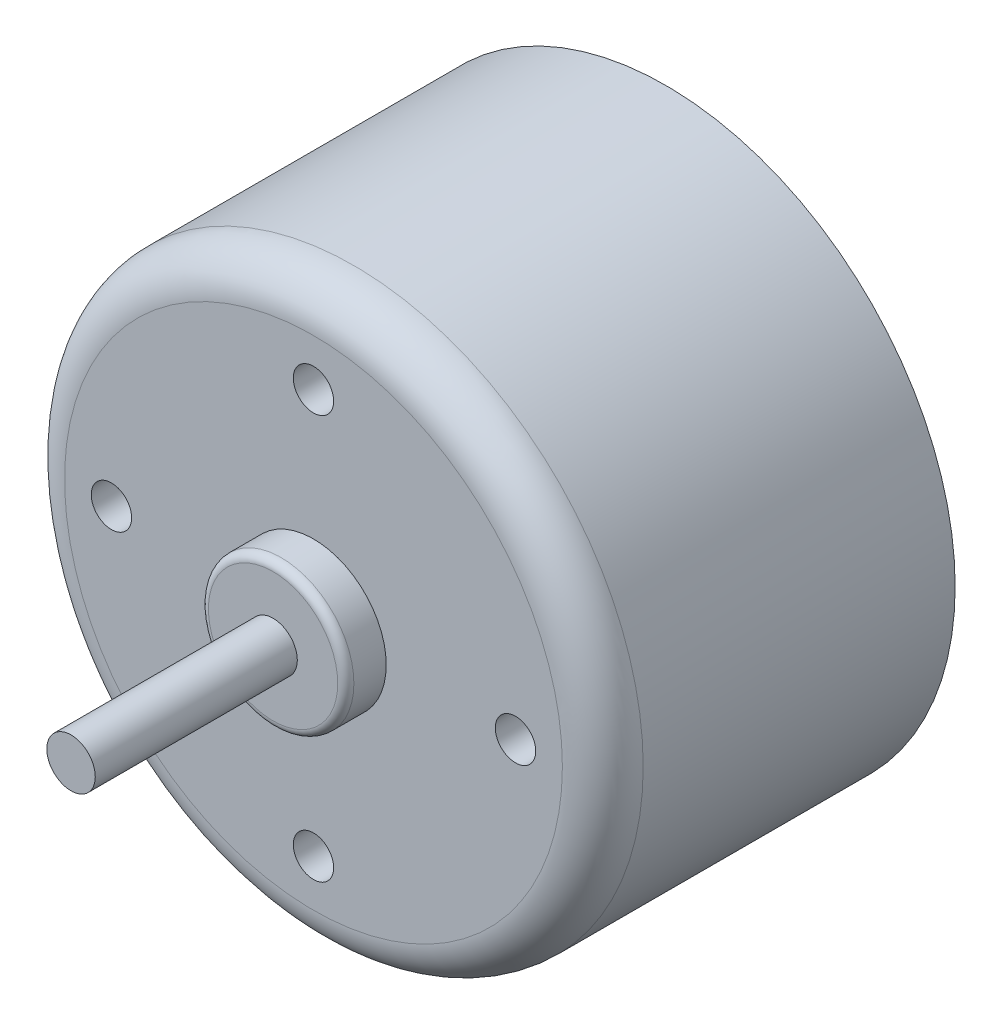
SolidWorks part; units mm, degrees
ref_plane "Front Plane" through (0, 0, 0) normal (0, 0, 1) x (1, 0, 0)
ref_plane "Top Plane" through (0, 0, 0) normal (0, 1, 0) x (1, 0, 0)
ref_plane "Right Plane" through (0, 0, 0) normal (1, 0, 0) x (0, 0, -1)
sketch "Sketch1" plane through (0, 0, 0) normal (0, 0, 1) x (1, 0, 0)
  circle A0 centre (0, 0) radius 17.9
  dimension "D1" = 35.8
extrude "Boss-Extrude1" add sketch "Sketch1" along normal blind 21.8
fillet "Fillet1" radius 2.5 1 edges at (17.9, 0, 21.8)
sketch "Sketch2" plane through (0, 0, 21.8) normal (0, 0, 1) x (1, 0, 0)
  circle A0 centre (0, 0) radius 4.5
  dimension "D1" = 9
extrude "Boss-Extrude2" add sketch "Sketch2" along normal blind 2.5
fillet "Fillet2" radius 0.5 1 edges at (4.5, 0, 24.3)
hole_wizard "M3x0.5 Tapped Hole1" positions "Sketch3" profile "Sketch4" tap size "M3x0.5" standard "ANSI Metric"
sketch "Sketch3" plane through (0, 0, 21.8) normal (0, 0, 1) x (1, 0, 0)
  circle A0 centre (0, 0) radius 12.5
  point P0 (0, 12.5)
  point P8 (0, -12.5)
  point P10 (12.5, 0)
  point P12 (-12.5, 0)
  dimension "D1" = 25
sketch "Sketch4" plane through (0, 12.5, 21.8) normal (1, 0, 0) x (0, -1, 0)
  line L0 (0, 0) -> (0, 8.3711)
  line L1 (0, 8.3711) -> (1.25, 7.62)
  line L2 (1.25, 7.62) -> (1.25, 0)
  line L5 (1.25, 0) -> (0, 0)
  line L10 (0, 8.3711) -> (-1.25, 7.62) construction
  line L11 (0, -6.35) -> (0, 107.95) construction
  dimension "Tap Drill Dia." = 2.5
  dimension "Tap Drill Depth" = 7.62
  dimension "Drill Angle" = 118
cosmetic thread "Hole Thread1" parameters "D1"=6.096, "D2"=3
cosmetic thread "Hole Thread2" parameters "D1"=6.096, "D2"=3
cosmetic thread "Hole Thread3" parameters "D1"=6.096, "D2"=3
cosmetic thread "Hole Thread4" parameters "D1"=6.096, "D2"=3
sketch "Sketch5" plane through (0, 0, 24.3) normal (0, 0, 1) x (1, 0, 0)
  circle A0 centre (0, 0) radius 1.5
  dimension "D1" = 3
extrude "Boss-Extrude3" add sketch "Sketch5" along normal offset from surface (12.5 mm away) 15 up to face at (1.25, 12.5, 21.8) offset beyond the face yes
sketch "Sketch6" plane through (0, 0, 0) normal (0, 0, -1) x (-1, 0, 0)
  circle A0 centre (0, 0) radius 6.35
  dimension "D1" = 12.7
extrude "Boss-Extrude4" add sketch "Sketch6" along normal blind 2
sketch "Sketch7" plane through (0, 0, -2) normal (0, 0, -1) x (-1, 0, 0)
  circle A0 centre (0, 0) radius 1.5
  dimension "D1" = 3
extrude "Boss-Extrude5" add sketch "Sketch7" along normal blind 1
